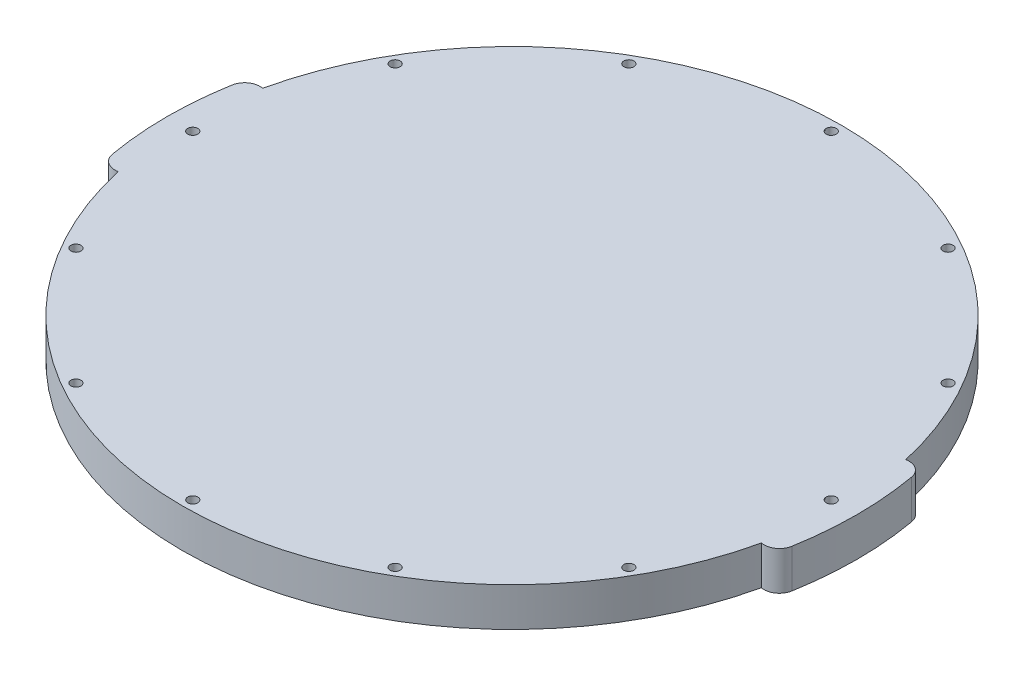
SolidWorks part; units mm, degrees
material "Acrylic (Medium-high impact)"
ref_plane "Front Plane" through (0, 0, 0) normal (0, 0, 1) x (1, 0, 0)
ref_plane "Top Plane" through (0, 0, 0) normal (0, 1, 0) x (1, 0, 0)
ref_plane "Right Plane" through (0, 0, 0) normal (1, 0, 0) x (0, 0, -1)
sketch "Sketch1" plane through (0, 0, 0) normal (0, 1, 0) x (1, 0, 0)
  line L0 (0, 0) -> (-111.234, 19.6136) construction
  line L1 (0, 0) -> (-139.7786, 0) construction
  line L2 (0, 0) -> (-111.234, -19.6136) construction
  line L3 (0, 0) -> (111.234, 19.6136) construction
  line L4 (0, 0) -> (111.234, -19.6136) construction
  circle A0 centre (0, 0) radius 104.55 construction
  circle A1 centre (0, 104.55) radius 1.65
  circle A2 centre (52.275, 90.543) radius 1.65
  circle A3 centre (90.543, 52.275) radius 1.65
  circle A4 centre (104.55, 0) radius 1.65
  circle A5 centre (90.543, -52.275) radius 1.65
  circle A6 centre (52.275, -90.543) radius 1.65
  circle A7 centre (0, -104.55) radius 1.65
  circle A8 centre (-52.275, -90.543) radius 1.65
  circle A9 centre (-90.543, -52.275) radius 1.65
  circle A10 centre (-104.55, 0) radius 1.65
  circle A11 centre (-90.543, 52.275) radius 1.65
  circle A12 centre (-52.275, 90.543) radius 1.65
  circle A13 centre (0, 0) radius 107.95 construction
  circle A14 centre (0, 0) radius 112.95 construction
  arc A15 (-111.234, -19.6136) -> (-111.234, 19.6136) centre (0, 0) cw
  arc A16 (111.234, -19.6136) -> (111.234, 19.6136) centre (0, 0) ccw
  arc A17 (-111.234, -19.6136) -> (-105.328, -23.6479) centre (-106.31, -18.7453) ccw
  arc A18 (-111.234, 19.6136) -> (-105.328, 23.6479) centre (-106.31, 18.7453) cw
  arc A19 (111.234, -19.6136) -> (105.328, -23.6479) centre (106.31, -18.7453) cw
  arc A20 (111.234, 19.6136) -> (105.328, 23.6479) centre (106.31, 18.7453) ccw
  arc A21 (-105.328, 23.6479) -> (105.328, 23.6479) centre (0, 0) cw
  arc A22 (105.328, -23.6479) -> (-105.328, -23.6479) centre (0, 0) cw
  point P30 (0, 0)
  dimension "D1" = 3.3
  dimension "D2" = 209.1
  dimension "D4" = 215.9
  dimension "D5" = 5
  dimension "D6" = 10
  dimension "D3" = 12
extrude "Boss-Extrude1" add sketch "Sketch1" along normal blind 12.7
fillet "Fillet1" [suppressed] radius 5
